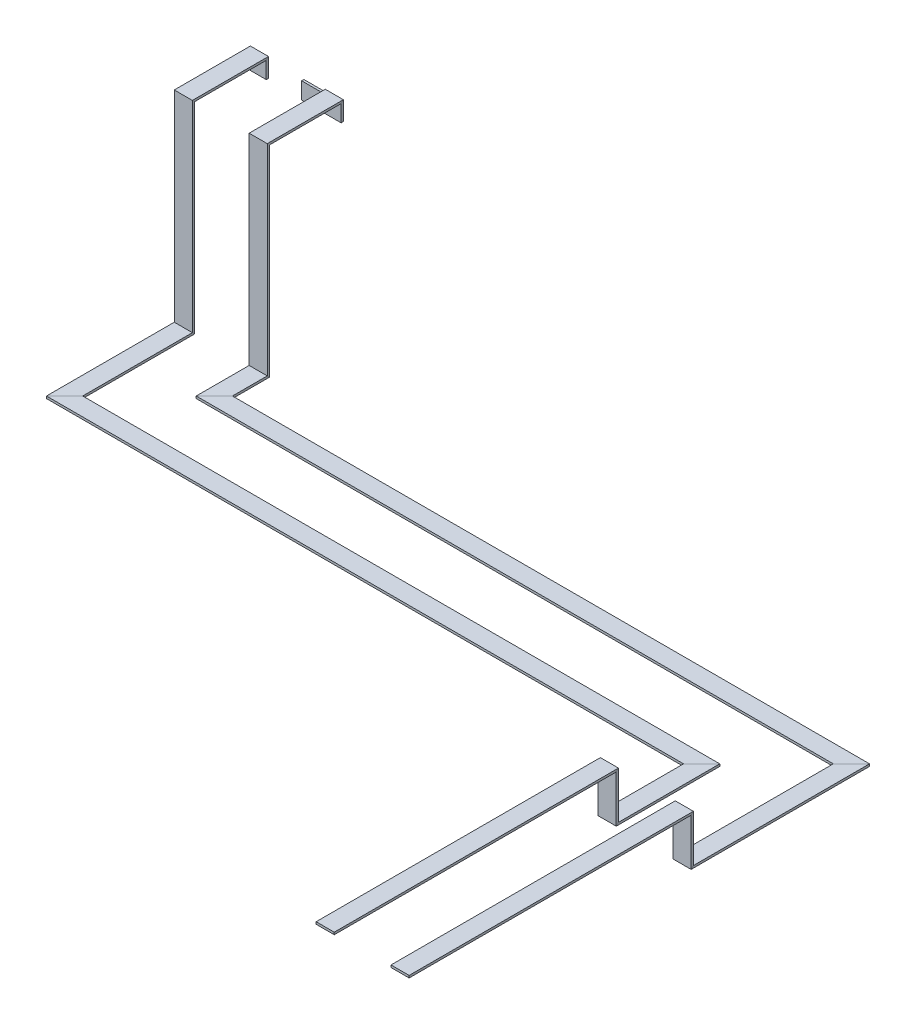
SolidWorks part; units mm, degrees
ref_plane "Alzado" through (0, 0, 0) normal (0, 0, 1) x (1, 0, 0)
ref_plane "Planta" through (0, 0, 0) normal (0, 1, 0) x (1, 0, 0)
ref_plane "Vista lateral" through (0, 0, 0) normal (1, 0, 0) x (0, 0, -1)
sketch "Croquis2" plane through (0, 0, 0) normal (0, 1, 0) x (1, 0, 0)
  line L1 (-25.4, 3.155) -> (25.4, 3.155)
  line L2 (-25.4, 3.155) -> (-25.4, -3.155)
  line L3 (-25.4, -3.155) -> (25.4, -3.155)
  line L4 (25.4, 3.155) -> (25.4, -3.155)
  line L5 (-25.4, 3.155) -> (25.4, -3.155) construction
  line L6 (-25.4, -3.155) -> (25.4, 3.155) construction
  line L7 (184.6, 3.155) -> (235.4, 3.155)
  line L8 (184.6, 3.155) -> (184.6, -3.155)
  line L9 (184.6, -3.155) -> (235.4, -3.155)
  line L10 (235.4, 3.155) -> (235.4, -3.155)
  line L11 (184.6, 3.155) -> (235.4, -3.155) construction
  line L12 (184.6, -3.155) -> (235.4, 3.155) construction
  point P0 (0, 0)
  point P6 (210, 0)
  dimension "D1" = 50.8
  dimension "D2" = 6.31
  dimension "D3" = 210
  dimension "D4" = 50.8
  dimension "D5" = 6.31
sketch3d "Croquis3D1"
  line L0 (0, 0, 0) -> (0, -567.24, 0)
  line L1 (0, -567.24, 0) -> (0, -567.24, 336.2)
  line L2 (0, -567.24, 336.2) -> (1786.7, -567.24, 336.2)
  line L3 (1786.7, -567.24, 336.2) -> (1786.7, -567.24, 598)
  line L4 (-25.4, 0, 0) -> (-25.4, -383.9185, 0) construction
  line L5 (-25.4, 0, -3.155) -> (-25.4, 0, 3.155) construction
  line L6 (-25.4, -383.9185, 0) -> (-25.4, -383.9185, 653.2834) construction
  line L7 (1786.7, -567.24, 598) -> (1786.7, -435.4728, 598)
  line L8 (1786.7, -435.4728, 598) -> (1786.7, -435.4728, 1392.0029)
  dimension "D1" = 567.24
  dimension "D2" = 336.2
  dimension "D3" = 1786.7
  dimension "D4" = 261.8
  dimension "D5" = 131.7672
  dimension "D6" = 794.0029
sweep "Barrer1" add profiles "Croquis2" path "Croquis3D1"
sketch "Croquis3" plane through (0, 0, -3.155) normal (0, 0, -1) x (-1, 0, 0)
  line L0 (-235.4, 0) -> (-235.4, -6.31)
  line L1 (-235.4, 0) -> (-235.4, -570.395) construction
  line L2 (-235.4, -6.31) -> (-184.6, -6.31)
  line L3 (-184.6, 0) -> (-184.6, -570.395) construction
  line L4 (-184.6, -6.31) -> (-184.6, 0)
  line L5 (-184.6, 0) -> (-235.4, 0)
  line L7 (-25.4, 0) -> (-25.4, -6.31)
  line L8 (-25.4, 0) -> (-25.4, -570.395) construction
  line L9 (-25.4, -6.31) -> (25.4, -6.31)
  line L10 (25.4, 0) -> (25.4, -570.395) construction
  line L11 (25.4, -6.31) -> (25.4, 0)
  line L12 (-25.4, 0) -> (25.4, 0) construction
  line L13 (25.4, 0) -> (-25.4, 0)
  dimension "D1" = 6.31
  dimension "D2" = 6.31
sketch3d "Croquis3D2"
  line L0 (25.4, -3.155, -3.155) -> (-0.201, -3.155, -3.155) construction
  line L1 (25.4, 0, -3.155) -> (25.4, -6.31, -3.155) construction
  line L2 (-0.201, -3.155, -3.155) -> (-0.201, -5.2746, -3.155) construction
  line L3 (-0.201, -3.155, -3.155) -> (-0.201, -3.155, -207.155)
  line L4 (-0.201, -3.155, -207.155) -> (-0.201, -53.155, -207.155)
  dimension "D1" = 204
  dimension "D2" = 50
sweep "Barrer4" add profiles "Croquis3" path "Croquis3D2"
sketch "Croquis4" plane through (0, 0, -210.31) normal (0, 0, -1) x (-1, 0, 0)
  line L0 (-184.6, 0) -> (-184.6, -53.155)
  line L1 (-184.6, -53.155) -> (-124.6, -53.155)
  line L2 (-124.6, -53.155) -> (-124.6, 0)
  line L3 (-124.6, 0) -> (-184.6, 0)
  dimension "D1" = 60
extrude "Saliente-Extruir1" add sketch "Croquis4" against normal blind 6.31
sketch "Croquis5" plane through (0, 0, -204) normal (0, 0, 1) x (1, 0, 0)
  line L0 (184.6, -6.31) -> (124.6, -6.31)
  line L1 (124.6, -53.155) -> (124.6, 0) construction
  line L2 (124.6, -6.31) -> (124.6, 0)
  line L3 (124.6, 0) -> (184.6, 0)
  line L4 (184.6, 0) -> (184.6, -6.31)
extrude "Cortar-Extruir1" cut sketch "Croquis5" against normal blind 6.31
sketch "Croquis6" plane through (0, -432.3178, 0) normal (0, 1, 0) x (1, 0, 0)
  circle A0 centre (1285.7, -1260.295) radius 4.75
  circle A1 centre (1495.7, -1260.295) radius 4.75
